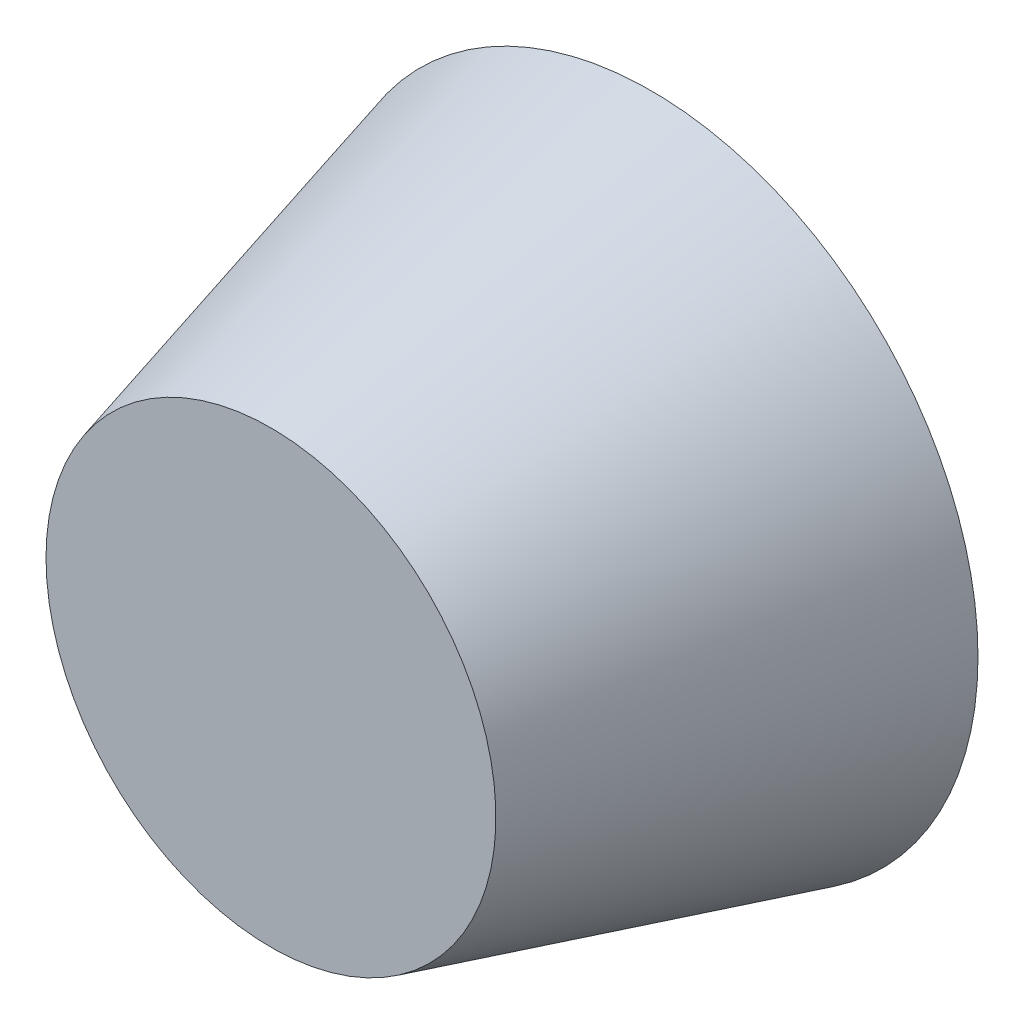
SolidWorks part; units mm, degrees
ref_plane "Front Plane" through (0, 0, 0) normal (0, 0, 1) x (1, 0, 0)
ref_plane "Top Plane" through (0, 0, 0) normal (0, 1, 0) x (1, 0, 0)
ref_plane "Right Plane" through (0, 0, 0) normal (1, 0, 0) x (0, 0, -1)
sketch "Sketch1" plane through (0, 0, 0) normal (0, 1, 0) x (1, 0, 0)
  line L0 (0, 0) -> (40, 0)
  line L1 (40, 0) -> (58.1173, 67.6148)
  line L2 (58.1173, 67.6148) -> (55.1173, 67.6148)
  line L3 (55.1173, 67.6148) -> (37.8038, 3)
  line L4 (37.8038, 3) -> (0, 3)
  line L5 (0, 3) -> (0, 0)
  point P3 (48.254, 73.1746)
  point P8 (0, 0)
  point P9 (64.4444, 73.1746)
  point P10 (61.5873, 67.4603)
  point P11 (65.0794, 78.254)
  point P12 (64.127, 73.1746)
  point P13 (55.1173, 67.6148)
  point P14 (0, 0)
  dimension "D1" = 40
  dimension "D2" = 70
  dimension "D3" = 3
  dimension "D4" = 3
  dimension "D5" = 105
revolve "Revolve1" add sketch "Sketch1" angle 360 about L5
